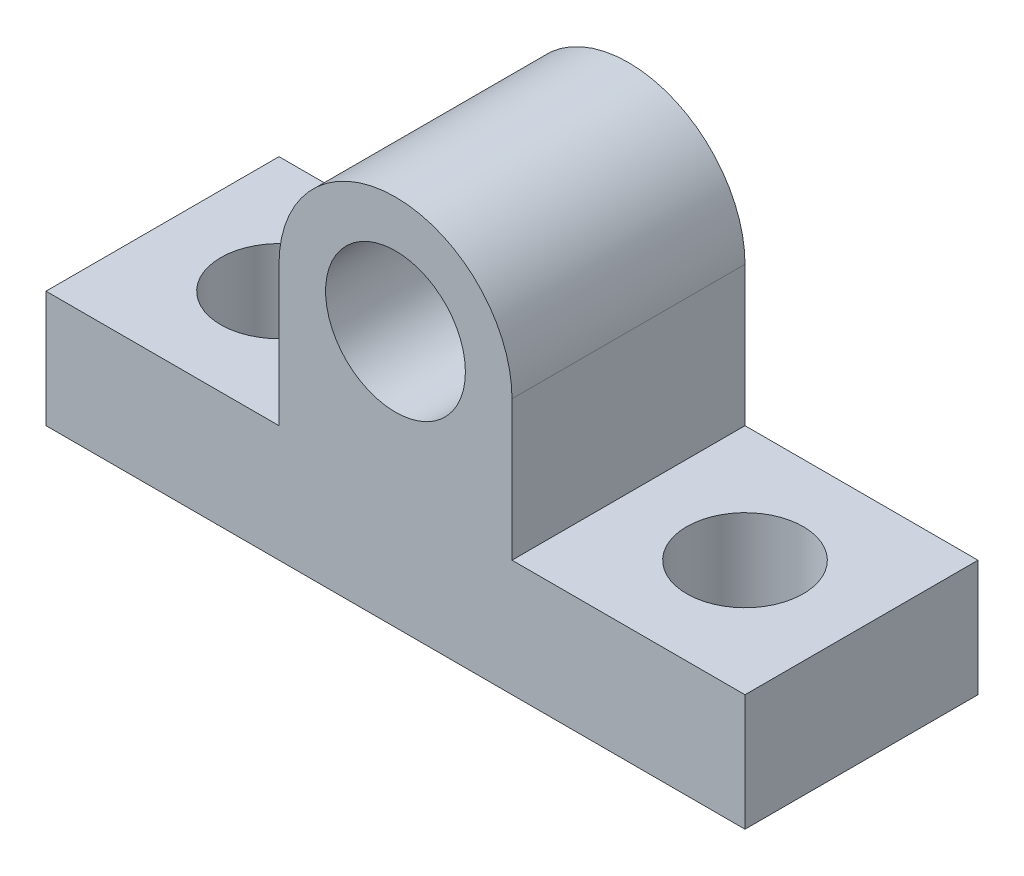
SolidWorks part; units mm, degrees
ref_plane "前视基准面" through (0, 0, 0) normal (0, 0, 1) x (1, 0, 0)
ref_plane "上视基准面" through (0, 0, 0) normal (0, 1, 0) x (1, 0, 0)
ref_plane "右视基准面" through (0, 0, 0) normal (1, 0, 0) x (0, 0, -1)
sketch "草图1" plane through (0, 0, 0) normal (0, 0, 1) x (1, 0, 0)
  line L0 (5, 0) -> (15, 0)
  line L1 (15, 0) -> (15, -5)
  line L2 (15, -5) -> (-15, -5)
  line L4 (5, 6) -> (5, 0)
  line L5 (-15, 0) -> (-15, -5)
  line L6 (-5, 0) -> (-15, 0)
  line L7 (-5, 6) -> (-5, 0)
  arc A0 (5, 6) -> (-5, 6) centre (0, 6) ccw
  circle A1 centre (0, 6) radius 3
  point P11 (0, -5)
  dimension "D3" = 10
  dimension "D4" = 6
  dimension "D1" = 6
  dimension "D2" = 5
extrude "凸台-拉伸1" add sketch "草图1" along normal blind 10
sketch "草图2" plane through (0, 0, 0) normal (0, 1, 0) x (1, 0, 0)
  line L0 (-5, 0) -> (-15, 0) construction
  line L4 (-15, -10) -> (-15, 0) construction
  circle A0 centre (-10, -5) radius 2.5
  point P2 (0, 0)
  point P7 (-15, -7.3224)
  point P8 (-15, -3.6219)
  point P9 (-6.9159, -5.1887)
  dimension "D1" = 5
  dimension "D2" = 5
extrude "切除-拉伸1" cut sketch "草图2" against normal blind 5 contours A0
sketch "草图3" plane through (0, 0, 0) normal (0, 1, 0) x (1, 0, 0)
  line L0 (15, -10) -> (15, 0) construction
  line L1 (15, -10) -> (5, -10) construction
  circle A0 centre (10, -5) radius 2.5
  dimension "D1" = 5
  dimension "D2" = 5
  dimension "D3" = 5
extrude "切除-拉伸2" cut sketch "草图3" against normal blind 5 contours A0
